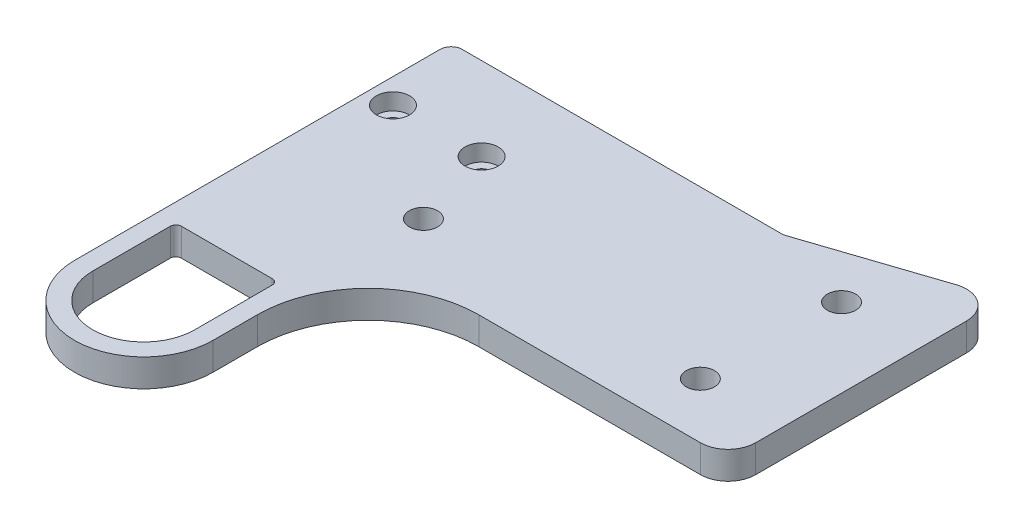
SolidWorks part; units mm, degrees
ref_plane "正面" through (0, 0, 0) normal (0, 0, 1) x (1, 0, 0)
ref_plane "平面" through (0, 0, 0) normal (0, 1, 0) x (1, 0, 0)
ref_plane "右側面" through (0, 0, 0) normal (1, 0, 0) x (0, 0, -1)
sketch "ｽｹｯﾁ1" plane through (0, 0, 0) normal (0, 1, 0) x (1, 0, 0)
  line L0 (0, 0) -> (180, 0) construction
  line L1 (180, 0) -> (180, 60) construction
  line L2 (0, 0) -> (0, -48)
  line L3 (0, -48) -> (25, -48) construction
  line L4 (25, -48) -> (25, -20)
  line L5 (180, 60) -> (0, 0) construction
  line L6 (0, 0) -> (90, 30)
  line L7 (90, 30) -> (90, -20)
  line L8 (90, -20) -> (25, -20)
  line L9 (0, -10) -> (90, -10) construction
  line L10 (90, 19.4591) -> (0, -10.5409) construction
  arc A0 (0, -48) -> (25, -48) centre (12.5, -48) ccw
  circle A1 centre (75.7698, 14.7157) radius 2.55
  circle A2 centre (75, -10) radius 2.55
  circle A3 centre (25, -10) radius 2.55
  circle A4 centre (12.5, -48) radius 7.5
  dimension "D5" = 25
  dimension "D9" = 15
  dimension "D12" = 5.1
  dimension "D13" = 15
  dimension "D1" = 60
  dimension "D2" = 180
  dimension "D3" = 20
  dimension "D4" = 90
  dimension "D6" = 28
  dimension "D7" = 10
  dimension "D8" = 10
  dimension "D10" = 25
  dimension "D11" = 15
extrude "ﾎﾞｽ - 押し出し1" add sketch "ｽｹｯﾁ1" along normal blind 5
fillet "ﾌｨﾚｯﾄ1" radius 20 1 edges at (25, 2.5, 20)
fillet "ﾌｨﾚｯﾄ2" radius 5 2 edges at (90, 2.5, -30) (90, 2.5, 20)
sketch "ｽｹｯﾁ2" plane through (0, 5, 0) normal (0, 1, 0) x (1, 0, 0)
  line L0 (3.3, -48) -> (3.3, -34)
  line L1 (4.3, -33) -> (20.7, -33)
  line L2 (21.7, -34) -> (21.7, -48)
  arc A0 (3.3, -48) -> (21.7, -48) centre (12.5, -48) ccw
  arc A1 (3.3, -34) -> (4.3, -33) centre (4.3, -34) cw
  arc A2 (20.7, -33) -> (21.7, -34) centre (20.7, -34) cw
  point P10 (21.7, -33)
  dimension "D1" = 9.2
  dimension "D3" = 1
  dimension "D2" = 15
extrude "ｶｯﾄ - 押し出し1" cut sketch "ｽｹｯﾁ2" against normal through all
sketch "ｽｹｯﾁ4" plane through (0, 5, 0) normal (0, 1, 0) x (1, 0, 0)
  line L0 (0, 0) -> (0, 20)
  line L1 (0, 20) -> (60, 20)
  line L2 (83.4189, 27.8063) -> (0, 0) construction
  line L3 (60, 20) -> (0, 0)
  dimension "D1" = 20
extrude "ﾎﾞｽ - 押し出し2" add sketch "ｽｹｯﾁ4" against normal up to surface (5 mm away) up to face at (12.5, 0, 39.7976)
sketch "ｽｹｯﾁ3" plane through (0, 5, 0) normal (0, 1, 0) x (1, 0, 0)
  line L0 (12.5, -60.5) -> (12.5, 5) construction
  line L1 (12.5, 5) -> (20.5, 5) construction
  line L2 (20.7, -33) -> (4.3, -33) construction
  arc A0 (0, -48) -> (25, -48) centre (12.5, -48) ccw construction
  circle A1 centre (20.5, 5) radius 1.55
  circle A2 centre (4.5, 5) radius 1.55
  dimension "D1" = 3.1
  dimension "D2" = 38
  dimension "D3" = 8
extrude "ｶｯﾄ - 押し出し2" cut sketch "ｽｹｯﾁ3" against normal through all
fillet "ﾌｨﾚｯﾄ3" radius 2 2 edges at (60, 2.5, -20) (0, 2.5, -20)
sketch "ｽｹｯﾁ5" plane through (0, 5, 0) normal (0, -1, 0) x (1, 0, 0)
  circle A0 centre (4.5, -5) radius 3
  circle A1 centre (20.5, -5) radius 3
  dimension "D1" = 6
extrude "ｶｯﾄ - 押し出し3" cut sketch "ｽｹｯﾁ5" along normal blind 3
